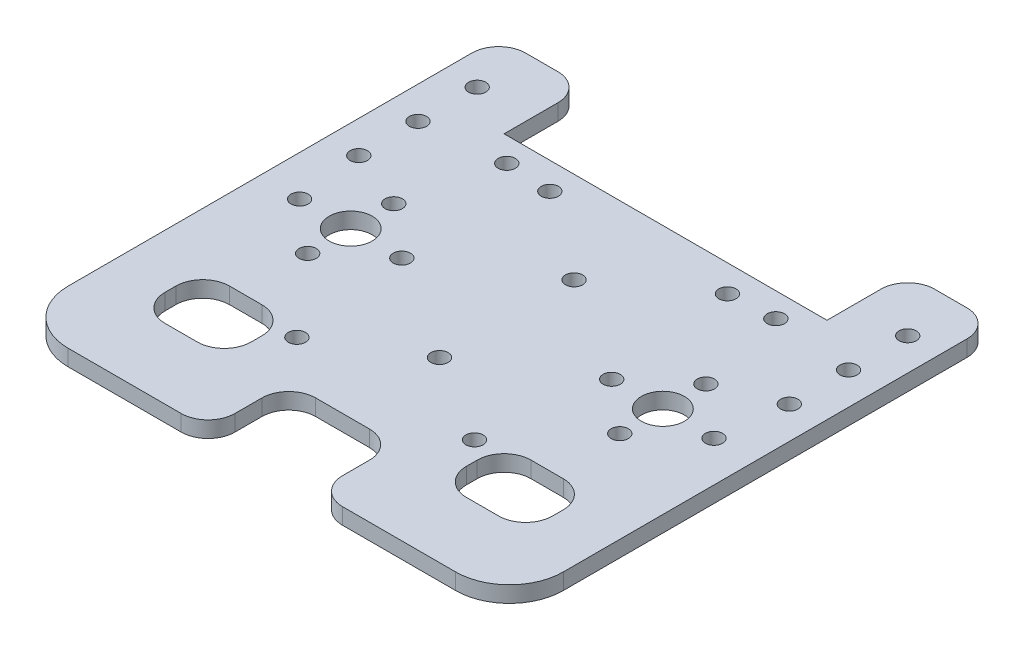
SolidWorks part; units mm, degrees
ref_plane "前视基准面" through (0, 0, 0) normal (0, 0, 1) x (1, 0, 0)
ref_plane "上视基准面" through (0, 0, 0) normal (0, 1, 0) x (1, 0, 0)
ref_plane "右视基准面" through (0, 0, 0) normal (1, 0, 0) x (0, 0, -1)
sketch "草图1" plane through (0, 0, 0) normal (0, 1, 0) x (1, 0, 0)
  line L0 (0, 153.466) -> (0, -161.6128) construction
  line L1 (36, 78) -> (36, 80)
  line L2 (31, 85) -> (25, 85)
  line L3 (20, 80) -> (20, 78)
  line L4 (25, 73) -> (31, 73)
  line L5 (-25, 85) -> (-31, 85)
  line L6 (-36, 80) -> (-36, 78)
  line L7 (-31, 73) -> (-25, 73)
  line L8 (-20, 78) -> (-20, 80)
  line L9 (5, 75) -> (-5, 75)
  line L10 (-10, 70) -> (-10, 65)
  line L11 (-15, 60) -> (-36, 60)
  line L12 (-46, 145) -> (-46, 70)
  line L13 (-35, 150) -> (-41, 150)
  line L14 (-30, 145) -> (-30, 135)
  line L15 (-30, 135) -> (30, 135)
  line L16 (30, 135) -> (30, 145)
  line L17 (41, 150) -> (35, 150)
  line L18 (46, 70) -> (46, 145)
  line L19 (10, 65) -> (10, 70)
  line L20 (36, 60) -> (15, 60)
  circle A0 centre (-40, 118) radius 1.6
  circle A1 centre (40, 129) radius 1.6
  circle A2 centre (-40, 129) radius 1.6
  circle A3 centre (40, 118) radius 1.6
  circle A4 centre (-16.5, 83) radius 1.6
  circle A5 centre (16.5, 83) radius 1.6
  circle A6 centre (-25, 130.5) radius 1.6
  circle A7 centre (25, 130.5) radius 1.6
  circle A8 centre (-16.5, 130) radius 1.6
  circle A9 centre (16.5, 130) radius 1.6
  circle A10 centre (0, 118) radius 1.6
  circle A11 centre (0, 93) radius 1.6
  circle A12 centre (-29, 105.5) radius 4
  circle A13 centre (-29, 97.5) radius 1.6
  circle A14 centre (-29, 113.5) radius 1.6
  circle A15 centre (-19.5, 105.5) radius 1.6
  circle A16 centre (-38.5, 105.5) radius 1.6
  circle A17 centre (38.5, 105.5) radius 1.6
  circle A18 centre (19.5, 105.5) radius 1.6
  circle A19 centre (29, 113.5) radius 1.6
  circle A20 centre (29, 97.5) radius 1.6
  circle A21 centre (29, 105.5) radius 4
  circle A22 centre (40, 140) radius 1.6
  circle A23 centre (-40, 140) radius 1.6
  arc A24 (31, 73) -> (36, 78) centre (31, 78) ccw
  arc A25 (36, 80) -> (31, 85) centre (31, 80) ccw
  arc A26 (25, 85) -> (20, 80) centre (25, 80) ccw
  arc A27 (20, 78) -> (25, 73) centre (25, 78) ccw
  arc A28 (-20, 80) -> (-25, 85) centre (-25, 80) ccw
  arc A29 (-31, 85) -> (-36, 80) centre (-31, 80) ccw
  arc A30 (-36, 78) -> (-31, 73) centre (-31, 78) ccw
  arc A31 (-25, 73) -> (-20, 78) centre (-25, 78) ccw
  arc A32 (10, 70) -> (5, 75) centre (5, 70) ccw
  arc A33 (-5, 75) -> (-10, 70) centre (-5, 70) ccw
  arc A34 (-15, 60) -> (-10, 65) centre (-15, 65) ccw
  arc A35 (-46, 70) -> (-36, 60) centre (-36, 70) ccw
  arc A36 (-41, 150) -> (-46, 145) centre (-41, 145) ccw
  arc A37 (-30, 145) -> (-35, 150) centre (-35, 145) ccw
  arc A38 (35, 150) -> (30, 145) centre (35, 145) ccw
  arc A39 (46, 145) -> (41, 150) centre (41, 145) ccw
  arc A40 (36, 60) -> (46, 70) centre (36, 70) ccw
  arc A41 (10, 65) -> (15, 60) centre (15, 65) ccw
extrude "凸台-拉伸1" add sketch "草图1" along normal blind 3
